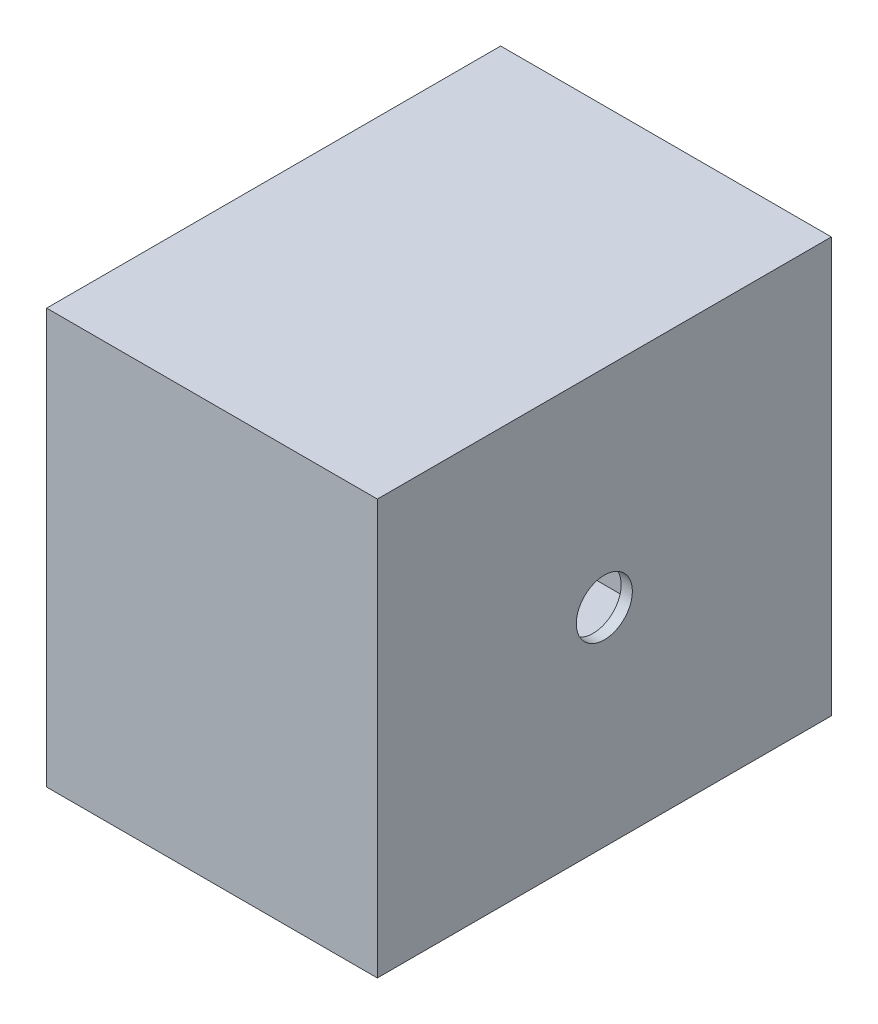
SolidWorks part; units mm, degrees
ref_plane "Front Plane" through (0, 0, 0) normal (0, 0, 1) x (1, 0, 0)
ref_plane "Top Plane" through (0, 0, 0) normal (0, 1, 0) x (1, 0, 0)
ref_plane "Right Plane" through (0, 0, 0) normal (1, 0, 0) x (0, 0, -1)
sketch "Sketch1" plane through (0, 0, 0) normal (1, 0, 0) x (0, 0, -1)
  line L1 (-40.5, 37) -> (40.5, 37)
  line L2 (-40.5, 37) -> (-40.5, -37)
  line L3 (-40.5, -37) -> (40.5, -37)
  line L4 (40.5, 37) -> (40.5, -37)
  line L5 (-40.5, 37) -> (40.5, -37) construction
  line L6 (-40.5, -37) -> (40.5, 37) construction
  point P0 (0, 0)
  dimension "D1" = 81
  dimension "D2" = 74
extrude "Boss-Extrude1" add sketch "Sketch1" along normal blind 59
sketch "Sketch3" plane through (0, 0, 0) normal (1, 0, 0) x (0, 0, -1)
  circle A0 centre (0, 0) radius 5
  dimension "D1" = 10
extrude "Cut-Extrude1" cut sketch "Sketch3" along normal blind 160
ref_plane "Plane1" through (0, 35, 0) normal (0, 1, 0) x (1, 0, 0)
sketch "Sketch4" plane through (0, 35, 0) normal (0, 1, 0) x (1, 0, 0)
  line L0 (59, 40.5) -> (0, 40.5) construction
  line L1 (2, 38.5) -> (57, 38.5)
  line L2 (2, 38.5) -> (2, -38.5)
  line L3 (2, -38.5) -> (57, -38.5)
  line L4 (57, 38.5) -> (57, -38.5)
  line L5 (59, -40.5) -> (0, -40.5) construction
  line L6 (59, 40.5) -> (59, -40.5) construction
  dimension "D1" = 55
  dimension "D2" = 2
  dimension "D3" = 2
  dimension "D4" = 2
extrude "Cut-Extrude2" cut sketch "Sketch4" against normal blind 70
